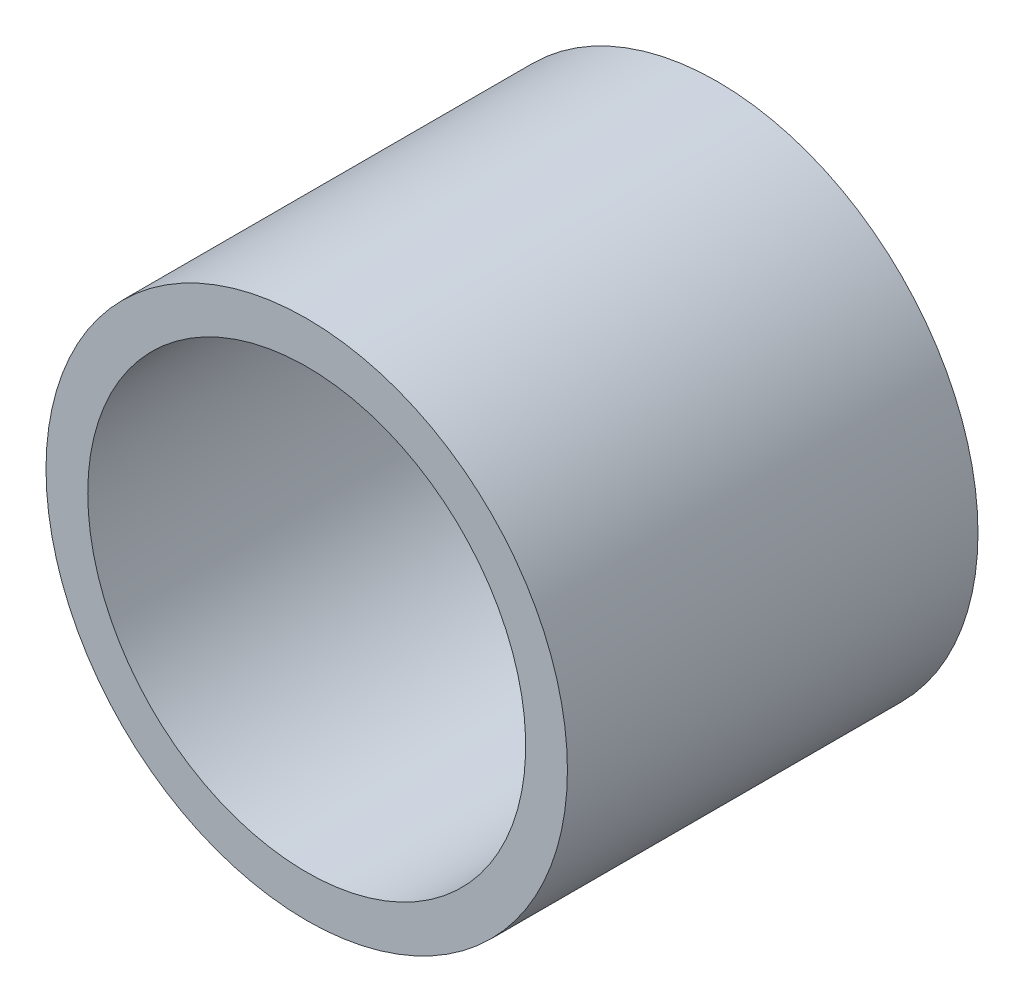
SolidWorks part; units mm, degrees
ref_plane "Front Plane" through (0, 0, 0) normal (0, 0, 1) x (1, 0, 0)
ref_plane "Top Plane" through (0, 0, 0) normal (0, 1, 0) x (1, 0, 0)
ref_plane "Right Plane" through (0, 0, 0) normal (1, 0, 0) x (0, 0, -1)
sketch "Sketch1" plane through (0, 0, 0) normal (0, 0, 1) x (1, 0, 0)
  circle A0 centre (0, 0) radius 24.1935
  circle A1 centre (0, 0) radius 20.32
  dimension "D1" = 40.64
  dimension "D2" = 48.387
extrude "Boss-Extrude1" add sketch "Sketch1" along normal blind 38.1 contours A0
